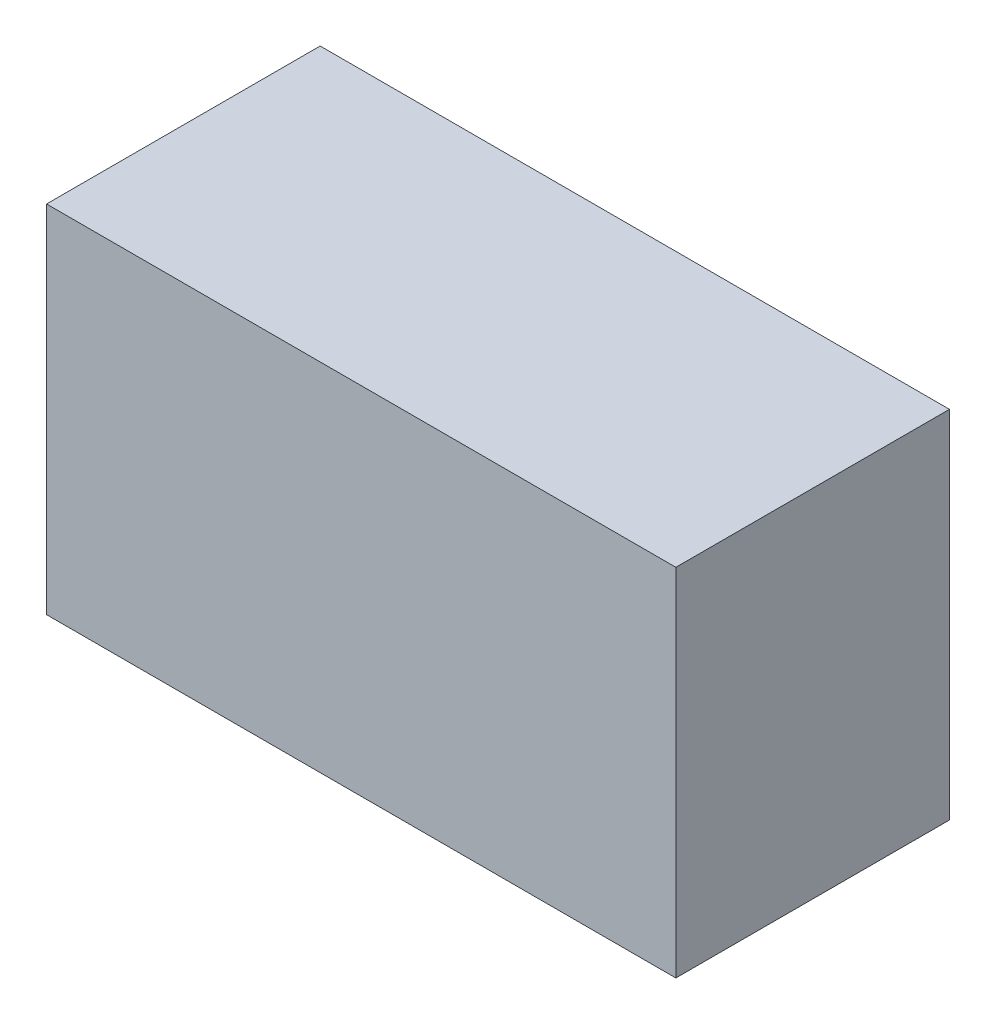
SolidWorks part; units mm, degrees
ref_plane "前视基准面" through (0, 0, 0) normal (0, 0, 1) x (1, 0, 0)
ref_plane "上视基准面" through (0, 0, 0) normal (0, 1, 0) x (1, 0, 0)
ref_plane "右视基准面" through (0, 0, 0) normal (1, 0, 0) x (0, 0, -1)
other "Configuration Table"
sketch "草图1" plane through (0, 0, 0) normal (0, 0, 1) x (1, 0, 0)
  line L1 (0, 0) -> (46, 0)
  line L2 (0, 0) -> (0, 26)
  line L3 (0, 26) -> (46, 26)
  line L4 (46, 0) -> (46, 26)
  dimension "D1" = 46
  dimension "D2" = 26
extrude "凸台-拉伸1" add sketch "草图1" along normal blind 20
